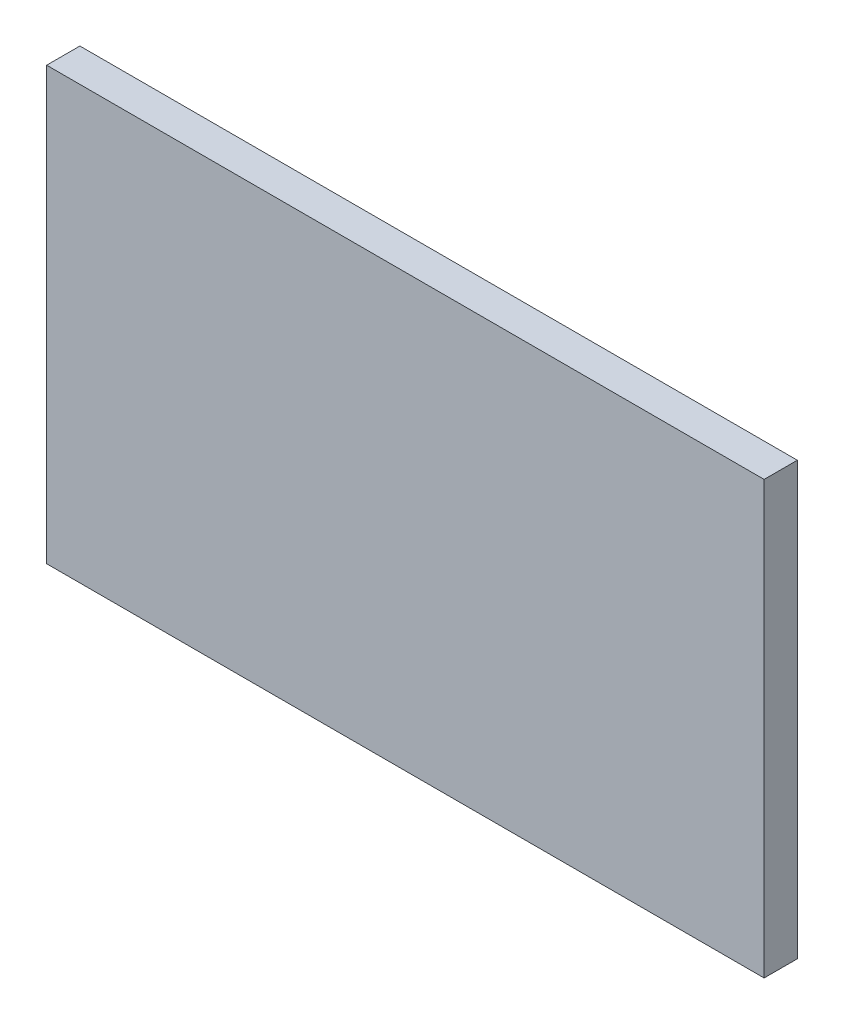
SolidWorks part; units mm, degrees
ref_plane "Front Plane" through (0, 0, 0) normal (0, 0, 1) x (1, 0, 0)
ref_plane "Top Plane" through (0, 0, 0) normal (0, 1, 0) x (1, 0, 0)
ref_plane "Right Plane" through (0, 0, 0) normal (1, 0, 0) x (0, 0, -1)
sketch "Sketch1" plane through (0, 0, 0) normal (0, 0, 1) x (1, 0, 0)
  line L1 (-50.1141, 32.8288) -> (57.8859, 32.8288)
  line L2 (-50.1141, 32.8288) -> (-50.1141, -32.1712)
  line L3 (-50.1141, -32.1712) -> (57.8859, -32.1712)
  line L4 (57.8859, 32.8288) -> (57.8859, -32.1712)
  dimension "D1" = 108
  dimension "D2" = 65
extrude "Boss-Extrude1" add sketch "Sketch1" along normal blind 5
